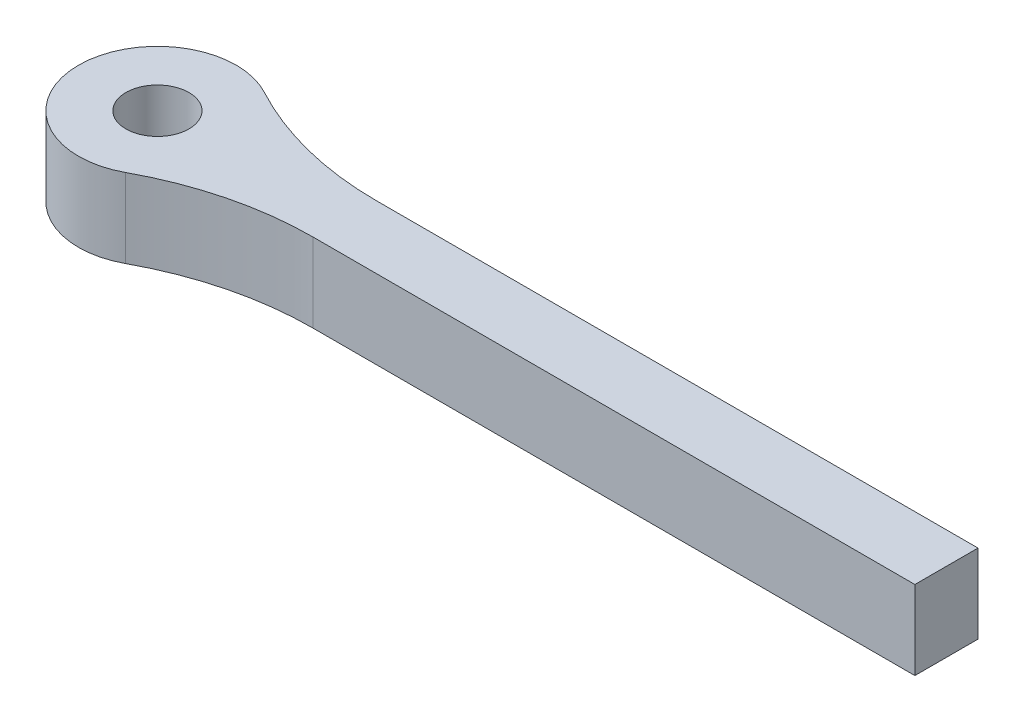
SolidWorks part; units mm, degrees
ref_plane "Front Plane" through (0, 0, 0) normal (0, 0, 1) x (1, 0, 0)
ref_plane "Top Plane" through (0, 0, 0) normal (0, 1, 0) x (1, 0, 0)
ref_plane "Right Plane" through (0, 0, 0) normal (1, 0, 0) x (0, 0, -1)
sketch "Sketch1" plane through (0, 0, 0) normal (0, 1, 0) x (1, 0, 0)
  line L1 (-58.1915, 3.5532) -> (16.8085, 3.5532)
  line L2 (-58.1915, 3.5532) -> (-58.1915, -2.4468)
  line L3 (-58.1915, -2.4468) -> (16.8085, -2.4468)
  line L4 (16.8085, 3.5532) -> (16.8085, -2.4468)
  circle A0 centre (-58.1915, 0.5532) radius 3
  circle A1 centre (-58.1915, 0.5532) radius 7.5
  dimension "D3" = 15
  dimension "D1" = 6
  dimension "D2" = 75
extrude "Boss-Extrude1" add sketch "Sketch1" along normal blind 7.5 contours L1 A1 L3 A0 | L3 A1 L1 A0 | A1 L3 L4 L1
fillet "Fillet1" radius 30 1 edges at (-51.3176, 3.75, 2.4468)
fillet "Fillet2" radius 30 1 edges at (-51.3176, 3.75, -3.5532)
